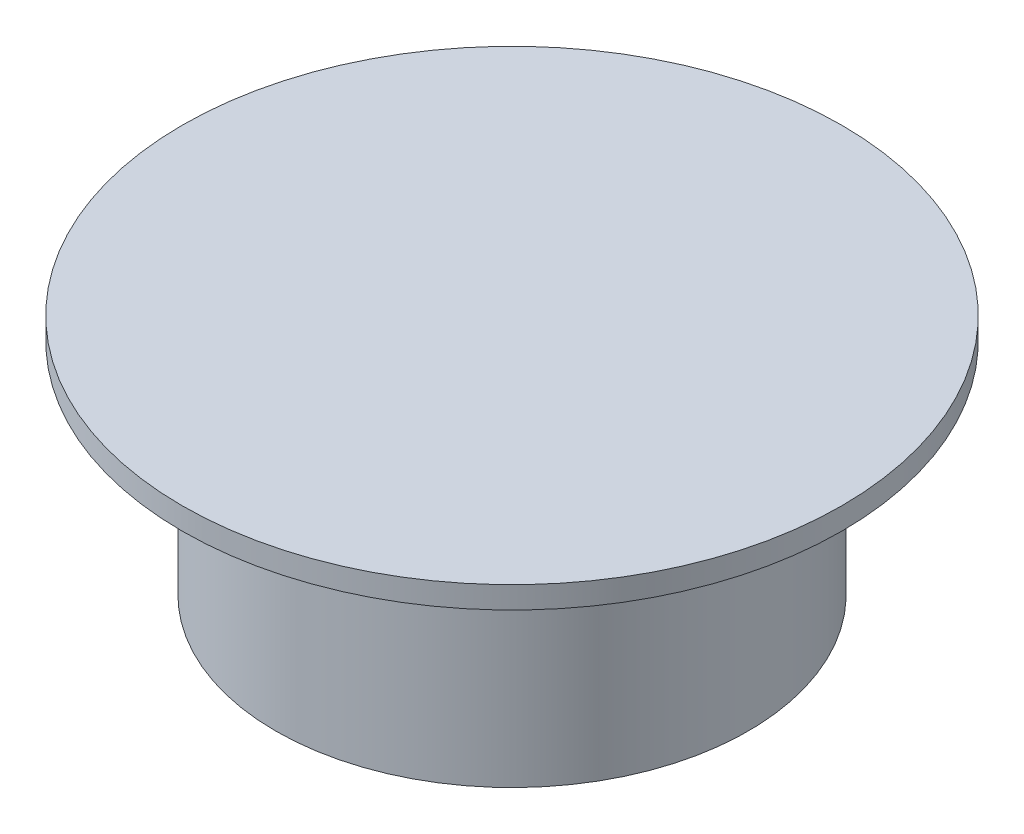
SolidWorks part; units mm, degrees
ref_plane "Front Plane" through (0, 0, 0) normal (0, 0, 1) x (1, 0, 0)
ref_plane "Top Plane" through (0, 0, 0) normal (0, 1, 0) x (1, 0, 0)
ref_plane "Right Plane" through (0, 0, 0) normal (1, 0, 0) x (0, 0, -1)
sketch "Sketch2" plane through (0, 0, 0) normal (0, 1, 0) x (1, 0, 0)
  circle A0 centre (0, 0) radius 10.75
  dimension "D1" = 21.5
extrude "Boss-Extrude1" add sketch "Sketch2" along normal blind 10
sketch "Sketch3" plane through (0, 10, 0) normal (0, 1, 0) x (1, 0, 0)
  circle A0 centre (0, 0) radius 15
  dimension "D1" = 30
extrude "Boss-Extrude2" add sketch "Sketch3" along normal blind 1
